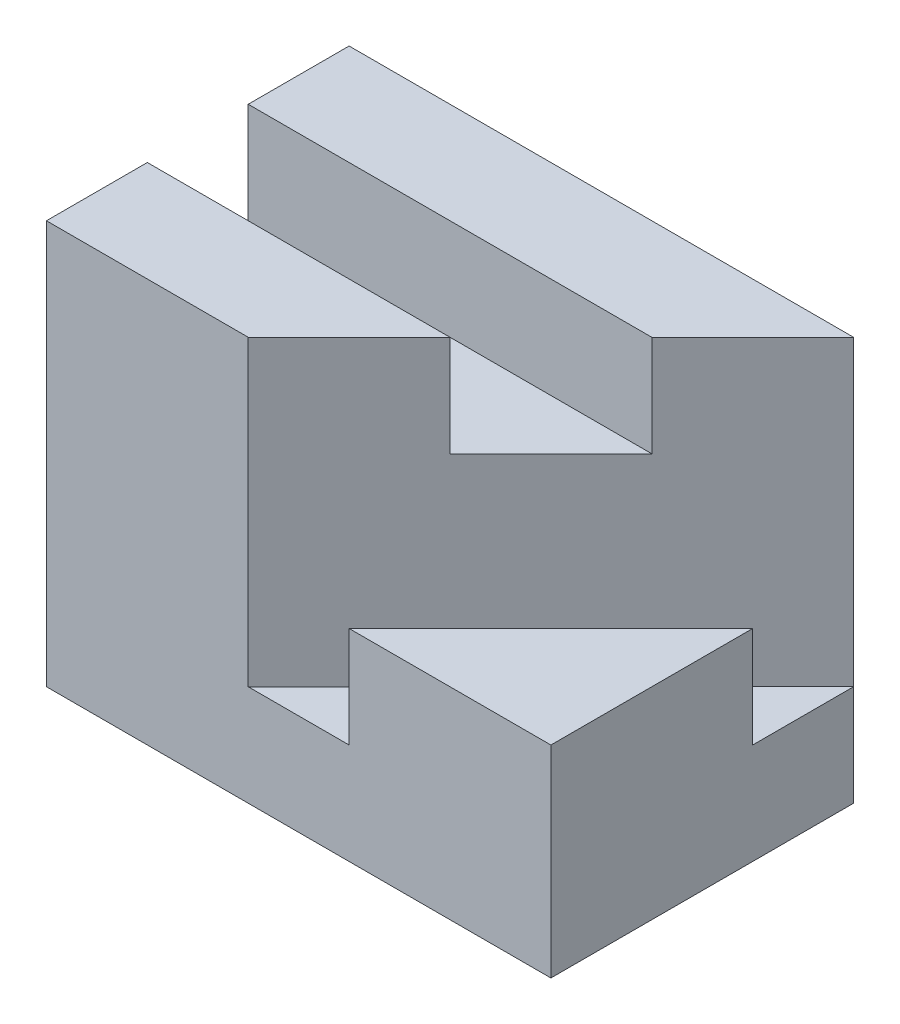
SolidWorks part; units mm, degrees
ref_plane "前基準面" through (0, 0, 0) normal (0, 0, 1) x (1, 0, 0)
ref_plane "上基準面" through (0, 0, 0) normal (0, 1, 0) x (1, 0, 0)
ref_plane "右基準面" through (0, 0, 0) normal (1, 0, 0) x (0, 0, -1)
sketch "草圖1" plane through (0, 0, 0) normal (1, 0, 0) x (0, 0, -1)
  line L0 (2.5, 10) -> (7.5, 10)
  line L1 (-7.5, 10) -> (-2.5, 10)
  line L2 (-7.5, 10) -> (-7.5, -10)
  line L3 (-7.5, -10) -> (7.5, -10)
  line L4 (7.5, 10) -> (7.5, -10)
  line L5 (-7.5, 10) -> (7.5, -10) construction
  line L6 (-7.5, -10) -> (7.5, 10) construction
  line L8 (-2.5, 10) -> (-2.5, 5)
  line L9 (-2.5, 5) -> (2.5, 5)
  line L10 (2.5, 10) -> (2.5, 5)
  point P0 (0, 0)
  point P6 (0, 5)
  point P10 (0, 0)
  point P12 (0, 0)
  point P13 (0.1551, 11.4392)
  point P14 (-2.5, 7.5)
  dimension "D1" = 20
  dimension "D2" = 15
  dimension "D3" = 5
  dimension "D4" = 2.5
  dimension "D5" = 5
extrude "填料-伸長1" add sketch "草圖1" against normal blind 25
sketch "草圖2" plane through (0, 10, 0) normal (0, 1, 0) x (1, 0, 0)
  line L0 (0, 2.5) -> (-10, -7.5)
  line L1 (0, 7.5) -> (0, 2.5) construction
  line L2 (-25, -7.5) -> (0, -7.5) construction
  line L3 (-15, -7.5) -> (0, 7.5)
  line L4 (0, 7.5) -> (0, 2.5)
  line L5 (-15, -7.5) -> (-10, -7.5)
  line L6 (0, -2.5) -> (0, -7.5) construction
  dimension "D1" = 10
  dimension "D2" = 5
extrude "除料-伸長2" cut sketch "草圖2" against normal blind 15 contours L0 L5 L3 L4
sketch "草圖3" plane through (0, 10, 0) normal (0, 1, 0) x (1, 0, 0)
  line L0 (-5, -2.5) -> (-10, -7.5)
  line L3 (0, -2.5) -> (0, 2.5)
  line L4 (0, 2.5) -> (-5, -2.5)
  line L5 (-5, -2.5) -> (0, -2.5)
  line L6 (0, -2.5) -> (0, 2.5)
  line L7 (0, 2.5) -> (-5, -2.5)
  line L8 (-5, -2.5) -> (0, -2.5)
  line L10 (0, -2.5) -> (-5, -2.5)
  line L11 (-5, -2.5) -> (-10, -7.5)
  line L12 (-10, -7.5) -> (0, -7.5)
  line L13 (0, -7.5) -> (0, -2.5)
  line L14 (0, -2.5) -> (-5, -2.5)
  line L15 (-5, -2.5) -> (-10, -7.5)
  line L16 (-10, -7.5) -> (0, -7.5)
  line L17 (0, -7.5) -> (0, -2.5)
  line M8 (0, -2.5) -> (-5, -2.5)
  line M9 (-5, -2.5) -> (-10, -7.5)
  line M10 (-10, -7.5) -> (0, -7.5)
  line M11 (0, -7.5) -> (0, -2.5)
  dimension "D1" = 0
  dimension "D2" = 0
extrude "除料-伸長3" cut sketch "草圖3" against normal blind 10 contours L6 L7 M8 | M11 M8 M9 M10
